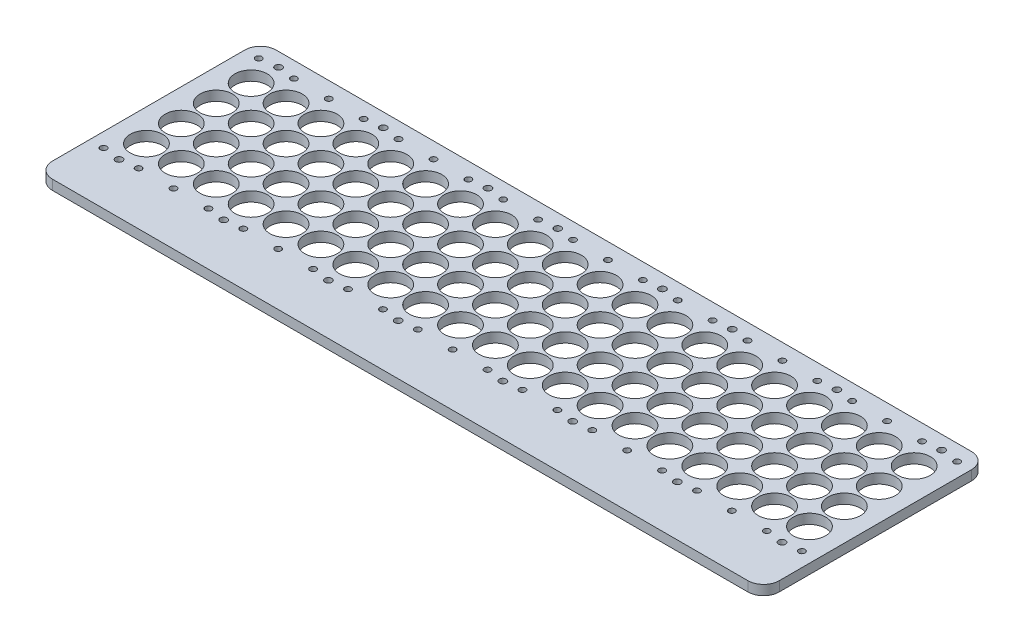
SolidWorks part; units mm, degrees
material "ABS"
ref_plane "X-Y Datum" through (0, 0, 0) normal (0, 0, 1) x (1, 0, 0)
ref_plane "X-Z Datum" through (0, 0, 0) normal (0, 1, 0) x (1, 0, 0)
ref_plane "Y-Z Datum" through (0, 0, 0) normal (1, 0, 0) x (0, 0, -1)
sketch "Sketch1" plane through (0, 0, 0) normal (0, 1, 0) x (1, 0, 0)
  line L0 (11.303, 19.5774) -> (22.606, 0) construction
  line L1 (0, 0) -> (0, 39.1547) construction
  line L2 (0, -43.0151) -> (0, 43.0151) construction
  line L3 (0, -10.5) -> (0, -28.28) construction
  line L4 (-10.5, 0) -> (-15.58, 0) construction
  line L5 (451.317, 58.6934) -> (456.397, 58.6934) construction
  line L6 (440.817, 69.1934) -> (440.817, 86.9734) construction
  line L8 (-15.58, -28.28) -> (456.397, -28.28)
  line L9 (-15.58, -28.28) -> (-15.58, 86.9734)
  line L10 (-15.58, 86.9734) -> (456.397, 86.9734)
  line L11 (456.397, -28.28) -> (456.397, 86.9734)
  circle A0 centre (0, 0) radius 10.5
  circle A1 centre (22.606, 0) radius 10.5
  circle A2 centre (45.212, 0) radius 10.5
  circle A3 centre (67.818, 0) radius 10.5
  circle A4 centre (90.424, 0) radius 10.5
  circle A5 centre (113.03, 0) radius 10.5
  circle A6 centre (135.636, 0) radius 10.5
  circle A7 centre (158.242, 0) radius 10.5
  circle A8 centre (180.848, 0) radius 10.5
  circle A9 centre (203.454, 0) radius 10.5
  circle A10 centre (226.06, 0) radius 10.5
  circle A11 centre (248.666, 0) radius 10.5
  circle A12 centre (271.272, 0) radius 10.5
  circle A13 centre (293.878, 0) radius 10.5
  circle A14 centre (316.484, 0) radius 10.5
  circle A15 centre (339.09, 0) radius 10.5
  circle A16 centre (361.696, 0) radius 10.5
  circle A17 centre (384.302, 0) radius 10.5
  circle A18 centre (406.908, 0) radius 10.5
  circle A19 centre (429.514, 0) radius 10.5
  circle A24 centre (33.909, 19.5774) radius 10.5
  circle A25 centre (56.515, 19.5774) radius 10.5
  circle A26 centre (79.121, 19.5774) radius 10.5
  circle A27 centre (101.727, 19.5774) radius 10.5
  circle A28 centre (124.333, 19.5774) radius 10.5
  circle A29 centre (146.939, 19.5774) radius 10.5
  circle A30 centre (169.545, 19.5774) radius 10.5
  circle A31 centre (192.151, 19.5774) radius 10.5
  circle A32 centre (214.757, 19.5774) radius 10.5
  circle A33 centre (237.363, 19.5774) radius 10.5
  circle A34 centre (259.969, 19.5774) radius 10.5
  circle A35 centre (282.575, 19.5774) radius 10.5
  circle A36 centre (305.181, 19.5774) radius 10.5
  circle A37 centre (327.787, 19.5774) radius 10.5
  circle A38 centre (350.393, 19.5774) radius 10.5
  circle A39 centre (372.999, 19.5774) radius 10.5
  circle A40 centre (395.605, 19.5774) radius 10.5
  circle A41 centre (418.211, 19.5774) radius 10.5
  circle A42 centre (440.817, 19.5774) radius 10.5
  circle A47 centre (11.303, 19.5774) radius 10.5
  circle A48 centre (0, 39.116) radius 10.5
  circle A49 centre (22.606, 39.116) radius 10.5
  circle A50 centre (45.212, 39.116) radius 10.5
  circle A51 centre (67.818, 39.116) radius 10.5
  circle A52 centre (90.424, 39.116) radius 10.5
  circle A53 centre (113.03, 39.116) radius 10.5
  circle A54 centre (135.636, 39.116) radius 10.5
  circle A55 centre (158.242, 39.116) radius 10.5
  circle A56 centre (180.848, 39.116) radius 10.5
  circle A57 centre (203.454, 39.116) radius 10.5
  circle A58 centre (226.06, 39.116) radius 10.5
  circle A59 centre (248.666, 39.116) radius 10.5
  circle A60 centre (271.272, 39.116) radius 10.5
  circle A61 centre (293.878, 39.116) radius 10.5
  circle A62 centre (316.484, 39.116) radius 10.5
  circle A63 centre (339.09, 39.116) radius 10.5
  circle A64 centre (361.696, 39.116) radius 10.5
  circle A65 centre (384.302, 39.116) radius 10.5
  circle A66 centre (406.908, 39.116) radius 10.5
  circle A67 centre (429.514, 39.116) radius 10.5
  circle A72 centre (33.909, 58.6934) radius 10.5
  circle A73 centre (56.515, 58.6934) radius 10.5
  circle A74 centre (79.121, 58.6934) radius 10.5
  circle A75 centre (101.727, 58.6934) radius 10.5
  circle A76 centre (124.333, 58.6934) radius 10.5
  circle A77 centre (146.939, 58.6934) radius 10.5
  circle A78 centre (169.545, 58.6934) radius 10.5
  circle A79 centre (192.151, 58.6934) radius 10.5
  circle A80 centre (214.757, 58.6934) radius 10.5
  circle A81 centre (237.363, 58.6934) radius 10.5
  circle A82 centre (259.969, 58.6934) radius 10.5
  circle A83 centre (282.575, 58.6934) radius 10.5
  circle A84 centre (305.181, 58.6934) radius 10.5
  circle A85 centre (327.787, 58.6934) radius 10.5
  circle A86 centre (350.393, 58.6934) radius 10.5
  circle A87 centre (372.999, 58.6934) radius 10.5
  circle A88 centre (395.605, 58.6934) radius 10.5
  circle A89 centre (418.211, 58.6934) radius 10.5
  circle A90 centre (440.817, 58.6934) radius 10.5
  circle A95 centre (11.303, 58.6934) radius 10.5
  circle A96 centre (0, 0) radius 8
  circle A97 centre (22.606, 0) radius 8
  circle A98 centre (0, 0) radius 4.7
  circle A99 centre (22.606, 0) radius 4.7
  dimension "D1" = 20
  dimension "D4" = 21
  dimension "D3" = 2
  dimension "D5" = 2.5
  dimension "D6" = 2.5
  dimension "D2" = 2
sketch "Sketch2" plane through (0, 0, 0) normal (0, 1, 0) x (1, 0, 0)
  line L0 (429.514, 78.318) -> (429.514, 96.098) construction
  line L1 (440.014, 67.818) -> (445.094, 67.818) construction
  line L2 (-15.58, -28.28) -> (444.9203, -28.28)
  line L3 (-15.58, -28.28) -> (-15.58, 94.5014)
  line L5 (444.9203, -28.28) -> (444.9203, 94.5014)
  line L6 (10.5, 22.606) -> (12.106, 22.606) construction
  line L7 (0, -17.77) -> (90.424, -17.77) construction
  line L8 (10.5, 67.818) -> (12.106, 67.818) construction
  line L9 (79.924, 0) -> (78.318, 0) construction
  line L10 (79.121, 0) -> (79.121, -17.77) construction
  line L11 (-23.6526, 33.909) -> (459.7333, 33.909) construction
  line L12 (0, -10.5) -> (0, -11.77) construction
  line L13 (0, -43.0151) -> (0, 43.0151) construction
  line L14 (11.303, 67.818) -> (11.303, 79.588)
  line L15 (-13.297, 96.098) -> (-13.297, 94.5014) construction
  line L16 (-15.58, 94.5014) -> (444.9203, 94.5014)
  line L17 (0, -10.5) -> (0, -17.77) construction
  circle A0 centre (0, 0) radius 10.5
  circle A1 centre (22.606, 0) radius 10.5
  circle A2 centre (45.212, 0) radius 10.5
  circle A3 centre (67.818, 0) radius 10.5
  circle A4 centre (90.424, 0) radius 10.5
  circle A5 centre (113.03, 0) radius 10.5
  circle A6 centre (135.636, 0) radius 10.5
  circle A7 centre (158.242, 0) radius 10.5
  circle A8 centre (180.848, 0) radius 10.5
  circle A9 centre (203.454, 0) radius 10.5
  circle A10 centre (226.06, 0) radius 10.5
  circle A11 centre (248.666, 0) radius 10.5
  circle A12 centre (271.272, 0) radius 10.5
  circle A13 centre (293.878, 0) radius 10.5
  circle A14 centre (316.484, 0) radius 10.5
  circle A15 centre (339.09, 0) radius 10.5
  circle A24 centre (22.606, 22.606) radius 10.5
  circle A25 centre (45.212, 22.606) radius 10.5
  circle A26 centre (67.818, 22.606) radius 10.5
  circle A27 centre (90.424, 22.606) radius 10.5
  circle A28 centre (113.03, 22.606) radius 10.5
  circle A29 centre (135.636, 22.606) radius 10.5
  circle A30 centre (158.242, 22.606) radius 10.5
  circle A31 centre (180.848, 22.606) radius 10.5
  circle A32 centre (203.454, 22.606) radius 10.5
  circle A33 centre (226.06, 22.606) radius 10.5
  circle A34 centre (248.666, 22.606) radius 10.5
  circle A35 centre (271.272, 22.606) radius 10.5
  circle A36 centre (293.878, 22.606) radius 10.5
  circle A37 centre (316.484, 22.606) radius 10.5
  circle A38 centre (339.09, 22.606) radius 10.5
  circle A47 centre (22.606, 45.212) radius 10.5
  circle A48 centre (45.212, 45.212) radius 10.5
  circle A49 centre (67.818, 45.212) radius 10.5
  circle A50 centre (90.424, 45.212) radius 10.5
  circle A51 centre (113.03, 45.212) radius 10.5
  circle A52 centre (135.636, 45.212) radius 10.5
  circle A53 centre (158.242, 45.212) radius 10.5
  circle A54 centre (180.848, 45.212) radius 10.5
  circle A55 centre (203.454, 45.212) radius 10.5
  circle A56 centre (226.06, 45.212) radius 10.5
  circle A57 centre (248.666, 45.212) radius 10.5
  circle A58 centre (271.272, 45.212) radius 10.5
  circle A59 centre (293.878, 45.212) radius 10.5
  circle A60 centre (316.484, 45.212) radius 10.5
  circle A61 centre (339.09, 45.212) radius 10.5
  circle A70 centre (22.606, 67.818) radius 10.5
  circle A71 centre (45.212, 67.818) radius 10.5
  circle A72 centre (67.818, 67.818) radius 10.5
  circle A73 centre (90.424, 67.818) radius 10.5
  circle A74 centre (113.03, 67.818) radius 10.5
  circle A75 centre (135.636, 67.818) radius 10.5
  circle A76 centre (158.242, 67.818) radius 10.5
  circle A77 centre (180.848, 67.818) radius 10.5
  circle A78 centre (203.454, 67.818) radius 10.5
  circle A79 centre (226.06, 67.818) radius 10.5
  circle A80 centre (248.666, 67.818) radius 10.5
  circle A81 centre (271.272, 67.818) radius 10.5
  circle A82 centre (293.878, 67.818) radius 10.5
  circle A83 centre (316.484, 67.818) radius 10.5
  circle A84 centre (339.09, 67.818) radius 10.5
  circle A93 centre (0, 22.606) radius 10.5
  circle A94 centre (0, 45.212) radius 10.5
  circle A95 centre (0, 67.818) radius 10.5
  circle A136 centre (361.696, 0) radius 10.5
  circle A137 centre (384.302, 0) radius 10.5
  circle A138 centre (406.908, 0) radius 10.5
  circle A139 centre (429.514, 0) radius 10.5
  circle A140 centre (361.696, 22.606) radius 10.5
  circle A141 centre (384.302, 22.606) radius 10.5
  circle A142 centre (406.908, 22.606) radius 10.5
  circle A143 centre (429.514, 22.606) radius 10.5
  circle A144 centre (361.696, 45.212) radius 10.5
  circle A145 centre (384.302, 45.212) radius 10.5
  circle A146 centre (406.908, 45.212) radius 10.5
  circle A147 centre (429.514, 45.212) radius 10.5
  circle A148 centre (361.696, 67.818) radius 10.5
  circle A149 centre (384.302, 67.818) radius 10.5
  circle A150 centre (406.908, 67.818) radius 10.5
  circle A151 centre (429.514, 67.818) radius 10.5
  circle A160 centre (0, 0) radius 4.7 construction
  circle A161 centre (22.606, 0) radius 4.7 construction
  circle A163 centre (0, -17.77) radius 6 construction
  circle A178 centre (67.818, -17.77) radius 6 construction
  circle A181 centre (135.636, -17.77) radius 6 construction
  circle A183 centre (180.848, -17.77) radius 6 construction
  circle A186 centre (248.666, -17.77) radius 6 construction
  circle A188 centre (293.878, -17.77) radius 6 construction
  circle A191 centre (361.696, -17.77) radius 6 construction
  circle A194 centre (429.514, -17.77) radius 6 construction
  circle A195 centre (22.606, -17.77) radius 6 [skipped]
  circle A196 centre (45.212, -17.77) radius 6 [skipped]
  circle A197 centre (90.424, -17.77) radius 6 [skipped]
  circle A198 centre (113.03, -17.77) radius 6 [skipped]
  circle A199 centre (316.484, -17.77) radius 6 [skipped]
  circle A200 centre (339.09, -17.77) radius 6 [skipped]
  circle A201 centre (384.302, -17.77) radius 6 [skipped]
  circle A202 centre (406.908, -17.77) radius 6 [skipped]
  circle A203 centre (203.454, -17.77) radius 6 [skipped]
  circle A204 centre (226.06, -17.77) radius 6 [skipped]
  circle A205 centre (158.242, -17.77) radius 6 [skipped]
  circle A206 centre (271.272, -17.77) radius 6 [skipped]
  circle A207 centre (429.514, 85.588) radius 6 construction
  circle A208 centre (361.696, 85.588) radius 6 construction
  circle A209 centre (293.878, 85.588) radius 6 construction
  circle A210 centre (248.666, 85.588) radius 6 construction
  circle A211 centre (180.848, 85.588) radius 6 construction
  circle A212 centre (135.636, 85.588) radius 6 construction
  circle A213 centre (67.818, 85.588) radius 6 construction
  circle A214 centre (0, 85.588) radius 6 construction
  circle A217 centre (11.303, 84.1854) radius 4.5974 construction
  circle A218 centre (11.303, 84.1854) radius 2.0447
  circle A219 centre (33.909, 84.1854) radius 2.0447
  circle A220 centre (56.515, 84.1854) radius 2.0447
  circle A221 centre (79.121, 84.1854) radius 2.0447
  circle A222 centre (101.727, 84.1854) radius 2.0447
  circle A223 centre (124.333, 84.1854) radius 2.0447
  circle A224 centre (146.939, 84.1854) radius 2.0447
  circle A225 centre (169.545, 84.1854) radius 2.0447
  circle A226 centre (192.151, 84.1854) radius 2.0447
  circle A227 centre (214.757, 84.1854) radius 2.0447
  circle A228 centre (237.363, 84.1854) radius 2.0447
  circle A229 centre (259.969, 84.1854) radius 2.0447
  circle A230 centre (282.575, 84.1854) radius 2.0447
  circle A231 centre (305.181, 84.1854) radius 2.0447
  circle A232 centre (327.787, 84.1854) radius 2.0447
  circle A233 centre (350.393, 84.1854) radius 2.0447
  circle A234 centre (372.999, 84.1854) radius 2.0447
  circle A235 centre (395.605, 84.1854) radius 2.0447
  circle A236 centre (418.211, 84.1854) radius 2.0447
  circle A237 centre (418.211, -16.3674) radius 2.0447
  circle A238 centre (395.605, -16.3674) radius 2.0447
  circle A239 centre (372.999, -16.3674) radius 2.0447
  circle A240 centre (350.393, -16.3674) radius 2.0447
  circle A241 centre (327.787, -16.3674) radius 2.0447
  circle A242 centre (305.181, -16.3674) radius 2.0447
  circle A243 centre (282.575, -16.3674) radius 2.0447
  circle A244 centre (259.969, -16.3674) radius 2.0447
  circle A245 centre (237.363, -16.3674) radius 2.0447
  circle A246 centre (214.757, -16.3674) radius 2.0447
  circle A247 centre (192.151, -16.3674) radius 2.0447
  circle A248 centre (169.545, -16.3674) radius 2.0447
  circle A249 centre (146.939, -16.3674) radius 2.0447
  circle A250 centre (124.333, -16.3674) radius 2.0447
  circle A251 centre (101.727, -16.3674) radius 2.0447
  circle A252 centre (79.121, -16.3674) radius 2.0447
  circle A253 centre (56.515, -16.3674) radius 2.0447
  circle A254 centre (33.909, -16.3674) radius 2.0447
  circle A255 centre (11.303, -16.3674) radius 2.0447
  circle A256 centre (0, -17.77) radius 1
  circle A259 centre (67.818, -17.77) radius 1
  circle A262 centre (135.636, -17.77) radius 1
  circle A264 centre (180.848, -17.77) radius 1
  circle A267 centre (248.666, -17.77) radius 1
  circle A269 centre (293.878, -17.77) radius 1
  circle A272 centre (361.696, -17.77) radius 1
  circle A275 centre (429.514, -17.77) radius 1
  circle A276 centre (22.606, -17.77) radius 1 [skipped]
  circle A277 centre (45.212, -17.77) radius 1 [skipped]
  circle A278 centre (90.424, -17.77) radius 1 [skipped]
  circle A279 centre (113.03, -17.77) radius 1 [skipped]
  circle A280 centre (158.242, -17.77) radius 1 [skipped]
  circle A281 centre (203.454, -17.77) radius 1 [skipped]
  circle A282 centre (226.06, -17.77) radius 1 [skipped]
  circle A283 centre (271.272, -17.77) radius 1 [skipped]
  circle A284 centre (316.484, -17.77) radius 1 [skipped]
  circle A285 centre (339.09, -17.77) radius 1 [skipped]
  circle A286 centre (384.302, -17.77) radius 1 [skipped]
  circle A287 centre (406.908, -17.77) radius 1 [skipped]
  circle A288 centre (429.514, 85.588) radius 1
  circle A289 centre (361.696, 85.588) radius 1
  circle A290 centre (293.878, 85.588) radius 1
  circle A291 centre (248.666, 85.588) radius 1
  circle A292 centre (180.848, 85.588) radius 1
  circle A293 centre (135.636, 85.588) radius 1
  circle A294 centre (67.818, 85.588) radius 1
  circle A295 centre (0, 85.588) radius 1
  dimension "D3" = 22.606
  dimension "D4" = 22.606
  dimension "D5" = 20
  dimension "D6" = 19
  dimension "D1" = 20
  dimension "D2" = 4
extrude "Boss-Extrude3" add sketch "Sketch2" along normal blind 6.35
sketch "Sketch4" plane through (0, 0, 0) normal (0, 1, 0) x (1, 0, 0)
  line L0 (0, -10.5) -> (0, -28.2611)
  line L1 (22.606, 57.318) -> (22.606, 55.712)
  line L2 (0, -43.0151) -> (0, 43.0151) construction
  line L3 (-10.5, 0) -> (-15.574, 0)
  line L4 (-3.4925, 0) -> (3.4925, 0) construction
  line L5 (429.514, 78.318) -> (429.514, 96.0117) construction
  line L6 (440.014, 67.818) -> (444.9297, 67.818)
  line L7 (33.106, 67.818) -> (34.712, 67.818)
  line L8 (-15.574, -28.2611) -> (444.9297, -28.2611)
  line L9 (-15.574, -28.2611) -> (-15.574, 96.0117)
  line L10 (-15.574, 96.0117) -> (444.9297, 96.0117)
  line L11 (444.9297, -28.2611) -> (444.9297, 96.0117)
  line L12 (33.909, 67.818) -> (33.909, 50.5991)
  line L13 (22.606, 56.515) -> (33.909, 56.515)
  line L14 (-10.5, 96.0117) -> (-10.5, 94.6757) construction
  line L15 (-15.574, 94.6757) -> (444.9297, 94.6757)
  circle A0 centre (0, 0) radius 10.5
  circle A1 centre (22.606, 0) radius 10.5
  circle A2 centre (45.212, 0) radius 10.5
  circle A3 centre (67.818, 0) radius 10.5
  circle A4 centre (90.424, 0) radius 10.5
  circle A5 centre (113.03, 0) radius 10.5
  circle A6 centre (135.636, 0) radius 10.5
  circle A7 centre (158.242, 0) radius 10.5
  circle A8 centre (180.848, 0) radius 10.5
  circle A9 centre (203.454, 0) radius 10.5
  circle A10 centre (226.06, 0) radius 10.5
  circle A11 centre (248.666, 0) radius 10.5
  circle A12 centre (271.272, 0) radius 10.5
  circle A13 centre (293.878, 0) radius 10.5
  circle A14 centre (316.484, 0) radius 10.5
  circle A15 centre (339.09, 0) radius 10.5
  circle A16 centre (22.606, 22.606) radius 10.5
  circle A17 centre (45.212, 22.606) radius 10.5
  circle A18 centre (67.818, 22.606) radius 10.5
  circle A19 centre (90.424, 22.606) radius 10.5
  circle A20 centre (113.03, 22.606) radius 10.5
  circle A21 centre (135.636, 22.606) radius 10.5
  circle A22 centre (158.242, 22.606) radius 10.5
  circle A23 centre (180.848, 22.606) radius 10.5
  circle A24 centre (203.454, 22.606) radius 10.5
  circle A25 centre (226.06, 22.606) radius 10.5
  circle A26 centre (248.666, 22.606) radius 10.5
  circle A27 centre (271.272, 22.606) radius 10.5
  circle A28 centre (293.878, 22.606) radius 10.5
  circle A29 centre (316.484, 22.606) radius 10.5
  circle A30 centre (339.09, 22.606) radius 10.5
  circle A31 centre (22.606, 45.212) radius 10.5
  circle A32 centre (45.212, 45.212) radius 10.5
  circle A33 centre (67.818, 45.212) radius 10.5
  circle A34 centre (90.424, 45.212) radius 10.5
  circle A35 centre (113.03, 45.212) radius 10.5
  circle A36 centre (135.636, 45.212) radius 10.5
  circle A37 centre (158.242, 45.212) radius 10.5
  circle A38 centre (180.848, 45.212) radius 10.5
  circle A39 centre (203.454, 45.212) radius 10.5
  circle A40 centre (226.06, 45.212) radius 10.5
  circle A41 centre (248.666, 45.212) radius 10.5
  circle A42 centre (271.272, 45.212) radius 10.5
  circle A43 centre (293.878, 45.212) radius 10.5
  circle A44 centre (316.484, 45.212) radius 10.5
  circle A45 centre (339.09, 45.212) radius 10.5
  circle A46 centre (22.606, 67.818) radius 10.5
  circle A47 centre (45.212, 67.818) radius 10.5
  circle A48 centre (67.818, 67.818) radius 10.5
  circle A49 centre (90.424, 67.818) radius 10.5
  circle A50 centre (113.03, 67.818) radius 10.5
  circle A51 centre (135.636, 67.818) radius 10.5
  circle A52 centre (158.242, 67.818) radius 10.5
  circle A53 centre (180.848, 67.818) radius 10.5
  circle A54 centre (203.454, 67.818) radius 10.5
  circle A55 centre (226.06, 67.818) radius 10.5
  circle A56 centre (248.666, 67.818) radius 10.5
  circle A57 centre (271.272, 67.818) radius 10.5
  circle A58 centre (293.878, 67.818) radius 10.5
  circle A59 centre (316.484, 67.818) radius 10.5
  circle A60 centre (339.09, 67.818) radius 10.5
  circle A91 centre (0, 22.606) radius 10.5
  circle A92 centre (0, 45.212) radius 10.5
  circle A93 centre (0, 67.818) radius 10.5
  circle A96 centre (361.696, 0) radius 10.5
  circle A97 centre (384.302, 0) radius 10.5
  circle A98 centre (406.908, 0) radius 10.5
  circle A99 centre (429.514, 0) radius 10.5
  circle A104 centre (361.696, 22.606) radius 10.5
  circle A105 centre (384.302, 22.606) radius 10.5
  circle A106 centre (406.908, 22.606) radius 10.5
  circle A107 centre (429.514, 22.606) radius 10.5
  circle A112 centre (361.696, 45.212) radius 10.5
  circle A113 centre (384.302, 45.212) radius 10.5
  circle A114 centre (406.908, 45.212) radius 10.5
  circle A115 centre (429.514, 45.212) radius 10.5
  circle A120 centre (361.696, 67.818) radius 10.5
  circle A121 centre (384.302, 67.818) radius 10.5
  circle A122 centre (406.908, 67.818) radius 10.5
  circle A123 centre (429.514, 67.818) radius 10.5
  circle A124 centre (33.909, 56.515) radius 3.8608
  circle A125 centre (33.909, 56.515) radius 5.4849
  dimension "D1" = 20
  dimension "D2" = 4
sketch "Sketch5" plane through (0, 0, 0) normal (0, 1, 0) x (1, 0, 0)
  circle A0 centre (0, 0) radius 10.5
hole_wizard "M4 Clearance Hole1" positions "Sketch6" profile "Sketch7" hole size "M4" standard "ANSI Metric" end condition through all
sketch "Sketch6" plane through (0, 6.35, 0) normal (0, 1, 0) x (1, 0, 0)
  point P0 (0, -17.77)
  point P3 (67.818, -17.77)
  point P6 (135.636, -17.77)
  point P9 (180.848, -17.77)
  point P12 (248.666, -17.77)
  point P15 (293.878, -17.77)
  point P18 (361.696, -17.77)
  point P21 (429.514, -17.77)
  point P25 (429.514, 85.588)
  point P28 (361.696, 85.588)
  point P31 (293.878, 85.588)
  point P34 (248.666, 85.588)
  point P37 (180.848, 85.588)
  point P40 (67.818, 85.588)
  point P43 (0, 85.588)
  point P46 (135.636, 85.588)
sketch "Sketch7" plane through (0, 6.35, 17.77) normal (1, 0, 0) x (0, 0, 1)
  line L0 (0, 0) -> (0, 6.35)
  line L1 (0, 6.35) -> (2.25, 6.35)
  line L2 (2.25, 6.35) -> (2.25, 0)
  line L5 (2.25, 0) -> (0, 0)
  line L11 (0, -6.35) -> (0, 107.95) construction
  dimension "Thru Hole Dia." = 4.5
  dimension "Thru Hole Depth" = 6.35
sketch "Sketch9" plane through (0, 6.35, 0) normal (0, 1, 0) x (1, 0, 0)
  line L0 (11.303, -21.0918) -> (11.303, -16.3674) construction
  line L1 (4.7, -21.0918) -> (17.906, -21.0918) construction
  line L2 (4.7, -21.0918) -> (4.7, 88.9098) construction
  line L3 (4.7, 88.9098) -> (17.906, 88.9098) construction
  line L4 (17.906, -21.0918) -> (17.906, 88.9098) construction
  line L5 (-4.7, 0) -> (-15.58, 0)
  line L6 (-55, 0) -> (55, 0) construction
  line L7 (-15.58, -28.28) -> (-15.58, 94.5014) construction
  circle A0 centre (0, 0) radius 4.7
  circle A1 centre (22.606, 0) radius 4.7
  circle A3 centre (11.303, 84.1854) radius 4.7244 construction
  circle A4 centre (11.303, -16.3674) radius 4.7244 construction
sketch "Sketch11" plane through (0, 6.35, 0) normal (0, 1, 0) x (1, 0, 0)
  line L0 (0, -11.77) -> (-11.77, -11.7587)
  line L1 (-10.5, 22.606) -> (-11.77, 22.606) construction
  line L2 (-11.77, 22.606) -> (-11.77, -11.7587)
  line L3 (0, 91.588) -> (-11.77, 91.588)
  line L4 (-11.77, 79.588) -> (-11.77, 22.606)
  line L7 (-15.58, -28.28) -> (-15.58, 94.5014) construction
  line L8 (-15.58, 91.588) -> (-15.58, -23.77)
  line L9 (-15.58, -23.77) -> (0, -23.77)
  line L10 (0, 79.588) -> (-11.77, 79.588)
  line L11 (-11.77, 91.588) -> (-15.58, 91.588)
  arc A0 (0, 79.588) -> (0, 91.588) centre (0, 85.588) ccw
  arc A1 (0, -23.77) -> (0, -11.77) centre (0, -17.77) ccw
  circle A3 centre (0, 22.606) radius 10.5 construction
sketch "Sketch12" plane through (0, 6.35, 0) normal (0, 1, 0) x (1, 0, 0)
  line L0 (-15.58, 94.5014) -> (-20.66, 94.5014)
  line L2 (-15.58, 94.5014) -> (-15.58, -28.28)
  line L3 (-15.58, -28.28) -> (-20.66, -28.28)
  line L4 (-20.66, 94.5014) -> (-20.66, -28.28)
  line L6 (444.9203, 94.5014) -> (444.9203, -28.28)
  line L7 (444.9203, -28.28) -> (450.174, -28.28)
  line L8 (450.174, 94.5014) -> (450.174, -28.28)
  line L9 (444.9203, 94.5014) -> (450.174, 94.5014)
extrude "Boss-Extrude4" add sketch "Sketch12" against normal up to surface (6.35 mm away) up to face at (0, 0, 20.02)
sketch "Sketch14" plane through (0, 6.35, 0) normal (0, 1, 0) x (1, 0, 0)
  line L0 (-18.2, 0) -> (-4.7, 0) construction
  line L1 (-4.7, 0) -> (-4.7, -22.5108) construction
  line L2 (-4.7, -22.5108) -> (-18.2, -22.5108) construction
  line L3 (-18.2, -22.5108) -> (-18.2, 100.6699) construction
  line L4 (-18.2, 100.6699) -> (-4.7, 100.6699) construction
  line L5 (-4.7, 100.6699) -> (-4.7, 0) construction
  line L6 (11.303, -16.3674) -> (-4.7, -16.3674) construction
  line L7 (11.303, -14.3227) -> (-4.7, -14.3227) construction
  line L8 (-18.2, 39.0795) -> (-4.7, 39.0795) construction
  line L9 (11.303, 86.2301) -> (11.303, 82.1407) construction
  line L10 (11.303, 84.1854) -> (-11.45, 84.1854) construction
  line L11 (214.757, -28.28) -> (214.757, 108.461) construction
  line L12 (-20.66, -28.28) -> (450.174, -28.28) construction
  circle A0 centre (0, 0) radius 4.7
  circle A1 centre (11.303, -16.3674) radius 2.0447 construction
  circle A2 centre (-11.45, -16.3674) radius 2.0447
  circle A3 centre (11.303, 84.1854) radius 2.0447 construction
  circle A4 centre (-11.45, 84.1854) radius 2.0447
  circle A5 centre (440.964, -16.3674) radius 2.0447
  circle A6 centre (440.964, 84.1854) radius 2.0447
extrude "Cut-Extrude1" cut sketch "Sketch14" against normal through all
sketch "Sketch15" plane through (0, 6.35, 0) normal (0, 1, 0) x (1, 0, 0)
  line L0 (-5.9995, -17.77) -> (-5.9995, -23.7695)
  line L1 (-20.66, -26.9445) -> (-20.66, 94.7625)
  line L2 (0, -26.9445) -> (-20.66, -26.9445)
  line L3 (-20.66, 94.5014) -> (-20.66, -28.28) construction
  line L4 (5.9995, -17.77) -> (5.9995, -26.9445)
  line L5 (5.9995, -26.9445) -> (0, -26.9445)
  line L7 (-17.485, 91.5875) -> (-17.485, -23.7695)
  line L8 (-17.485, -23.7695) -> (-5.9995, -23.7695)
  line L9 (0, 85.588) -> (0, -17.77) construction
  line L10 (0, 33.909) -> (-14.3772, 33.909) construction
  line L11 (5.9995, 85.588) -> (5.9995, 94.7625)
  line L12 (5.9995, 94.7625) -> (0, 94.7625)
  line L13 (0, 94.7625) -> (-20.66, 94.7625)
  line L14 (-17.485, 91.5875) -> (-5.9995, 91.5875)
  line L15 (-5.9995, 85.588) -> (-5.9995, 91.5875)
  arc A0 (5.9995, -17.77) -> (-5.9995, -17.77) centre (0, -17.77) ccw
  circle A1 centre (0, -17.77) radius 2.6251
  arc A2 (5.9995, 85.588) -> (-5.9995, 85.588) centre (0, 85.588) cw
sketch "Sketch16" plane through (0, 6.35, 0) normal (0, 1, 0) x (1, 0, 0)
  line L5 (-20.66, -28.28) -> (450.174, -28.28)
  line L6 (-20.66, -28.28) -> (-20.66, -50.3882)
  line L7 (-20.66, -50.3882) -> (450.174, -50.3882)
  line L8 (450.174, -28.28) -> (450.174, -50.3882)
extrude "Boss-Extrude5" add sketch "Sketch16" against normal up to surface (6.35 mm away) up to face at (440.964, 0, -86.2301)
fillet "Fillet2" radius 10.16 2 edges at (450.174, 3.175, -94.5014) (-20.66, 3.175, -94.5014)
fillet "Fillet3" radius 10.16 2 edges at (-20.66, 3.175, 50.3882) (450.174, 3.175, 50.3882)
